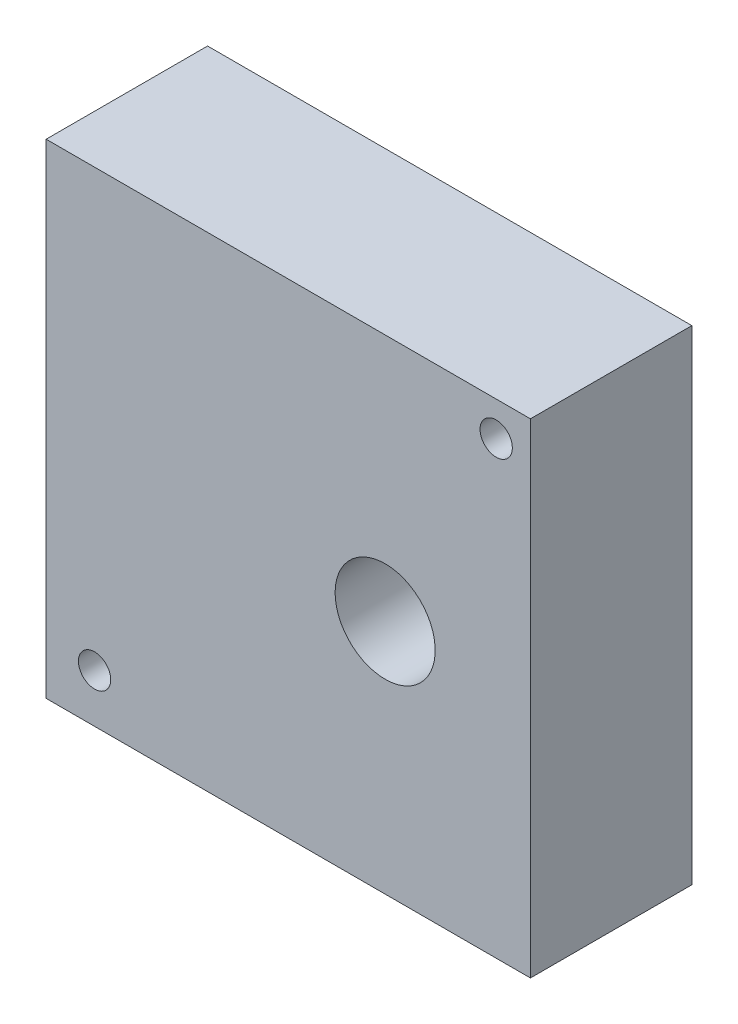
SolidWorks part; units mm, degrees
ref_plane "Front Plane" through (0, 0, 0) normal (0, 0, 1) x (1, 0, 0)
ref_plane "Top Plane" through (0, 0, 0) normal (0, 1, 0) x (1, 0, 0)
ref_plane "Right Plane" through (0, 0, 0) normal (1, 0, 0) x (0, 0, -1)
sketch "Sketch1" plane through (0, 0, 0) normal (0, 0, 1) x (1, 0, 0)
  line L1 (-15, 15) -> (15, 15)
  line L2 (-15, 15) -> (-15, -15)
  line L3 (-15, -15) -> (15, -15)
  line L4 (15, 15) -> (15, -15)
  line L5 (-15, 15) -> (15, -15) construction
  line L6 (-15, -15) -> (15, 15) construction
  point P0 (0, 0)
  dimension "D1" = 30
  dimension "D2" = 30
extrude "Boss-Extrude1" add sketch "Sketch1" along normal blind 10
sketch "Sketch2" plane through (0, 0, 10) normal (0, 0, 1) x (1, 0, 0)
  line L1 (-15, 15) -> (15, 15)
  line L2 (-15, 15) -> (-15, -15)
  line L3 (-15, -15) -> (15, -15)
  line L4 (15, 15) -> (15, -15)
  line L5 (-15, 15) -> (15, -15) construction
  line L6 (-15, -15) -> (15, 15) construction
  line L7 (10, 10) -> (-10, 10)
  line L8 (10, 10) -> (10, -10)
  line L9 (10, -10) -> (-10, -10)
  line L10 (-10, 10) -> (-10, -10)
  line L11 (10, 10) -> (-10, -10) construction
  line L12 (10, -10) -> (-10, 10) construction
  line L13 (0, 0) -> (0, -3.5) construction
  line L14 (0, 0) -> (0, 3.5) construction
  line L15 (-2.5, 7.2488) -> (2.5, 7.2488)
  line L16 (-2.5, 7.2488) -> (-2.5, -7.2488)
  line L17 (-2.5, -7.2488) -> (2.5, -7.2488)
  line L18 (2.5, 7.2488) -> (2.5, -7.2488)
  line L19 (-2.5, 7.2488) -> (2.5, -7.2488) construction
  line L20 (-2.5, -7.2488) -> (2.5, 7.2488) construction
  line L21 (-2.5, 3.5) -> (2.5, 3.5)
  line L22 (-2.5, 3.5) -> (-2.5, -3.5)
  line L23 (-2.5, -3.5) -> (2.5, -3.5)
  line L24 (2.5, 3.5) -> (2.5, -3.5)
  line L25 (-2.5, 3.5) -> (2.5, -3.5) construction
  line L26 (-2.5, -3.5) -> (2.5, 3.5) construction
  point P0 (0, 0)
  point P7 (0, 0)
  line M18 (15, -15) -> (15, 15)
  line M19 (15, 15) -> (-15, 15)
  line M20 (-15, 15) -> (-15, -15)
  line M21 (-15, -15) -> (15, -15)
  dimension "D1" = 20
  dimension "D2" = 20
  dimension "D3" = 3.5
  dimension "D4" = 3.5
  dimension "D5" = 7
  dimension "D6" = 5
  dimension "D7" = 5
extrude "Boss-Extrude2" add sketch "Sketch2" along normal blind 10 separate body contours L10 L7 L8 L9 M21 M18 M19 M20 | L16 L21 L18 L15 | L23 L16 L17 L18
sketch "Sketch3" plane through (0, 0, 20) normal (0, 0, 1) x (1, 0, 0)
  line L1 (-15, 15) -> (15, 15)
  line L2 (-15, 15) -> (-15, -15)
  line L3 (-15, -15) -> (15, -15)
  line L4 (15, 15) -> (15, -15)
extrude "Boss-Extrude3" add sketch "Sketch3" along normal blind 10 separate body
sketch "Sketch4" plane through (0, 0, 30) normal (0, 0, 1) x (1, 0, 0)
  line L1 (-15, 15) -> (-15, -15) construction
  line L3 (-15, 0) -> (-6, 0) construction
  circle A0 centre (-6, 0) radius 3.1
  dimension "D1" = 9
sketch "Sketch5" plane through (0, 0, 0) normal (0, 0, -1) x (-1, 0, 0)
  line L0 (-15, -0.3729) -> (-6, -0.3729) construction
  line L1 (-15, -15) -> (-15, 15) construction
  circle A0 centre (-6, -0.3729) radius 3.1
  dimension "D1" = 9
extrude "Cut-Extrude1" cut sketch "Sketch4" against normal blind 10
extrude "Cut-Extrude2" cut sketch "Sketch5" against normal blind 10 contours A0
sketch "Sketch8" plane through (0, 0, 30) normal (0, 0, 1) x (1, 0, 0)
  line L0 (-15, -15) -> (-12, -12) construction
  line L1 (-15, -15) -> (15, -15) construction
  line L2 (15, 15) -> (12.8787, 12.8787) construction
  line L3 (15, 15) -> (-15, 15) construction
  circle A0 centre (-12, -12) radius 1
  circle A1 centre (12.8787, 12.8787) radius 1
  dimension "D1" = 3
  dimension "D2" = 45
  dimension "D3" = 3
  dimension "D4" = 45
extrude "Cut-Extrude3" cut sketch "Sketch8" against normal up to surface (30 mm away)
delete or keep bodies "Body-Delete/Keep 1" type delete bodies bodies 110 111
delete or keep bodies "Body-Delete/Keep 2" type delete bodies bodies 103 104
